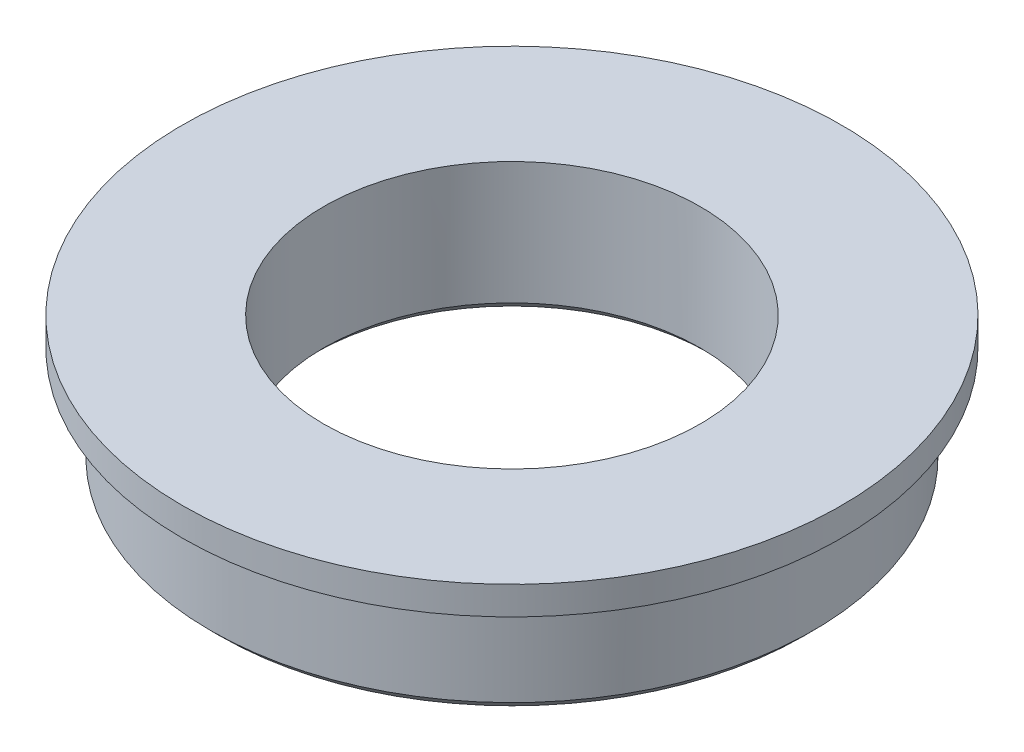
SolidWorks part; units mm, degrees
material "合金钢"
ref_plane "前视基准面" through (0, 0, 0) normal (0, 0, 1) x (1, 0, 0)
ref_plane "上视基准面" through (0, 0, 0) normal (0, 1, 0) x (1, 0, 0)
ref_plane "右视基准面" through (0, 0, 0) normal (1, 0, 0) x (0, 0, -1)
sketch "草图1" plane through (0, 0, 0) normal (0, 0, 1) x (1, 0, 0)
  line L0 (0, 90.7072) -> (0, -72.7292) construction
  line L1 (-104.5993, 0) -> (121.9235, 0) construction
  line L2 (-10, 0) -> (-10, 7)
  line L3 (-10, 7) -> (-17.5, 7)
  line L4 (-17.5, 7) -> (-17.5, 5.5)
  line L5 (-17.5, 5.5) -> (-16, 5.5)
  line L6 (-16, 5.5) -> (-16, 0)
  line L7 (-16, 0) -> (-10, 0)
  dimension "D1" = 20
  dimension "D2" = 32
  dimension "D3" = 7
  dimension "D4" = 35
  dimension "D5" = 1.5
revolve "旋转1" add sketch "草图1" angle 360 about L0
chamfer "倒角1" distance 0.5 angle 45 2 edges at (0, 0, 10) (0, 0, 16)
